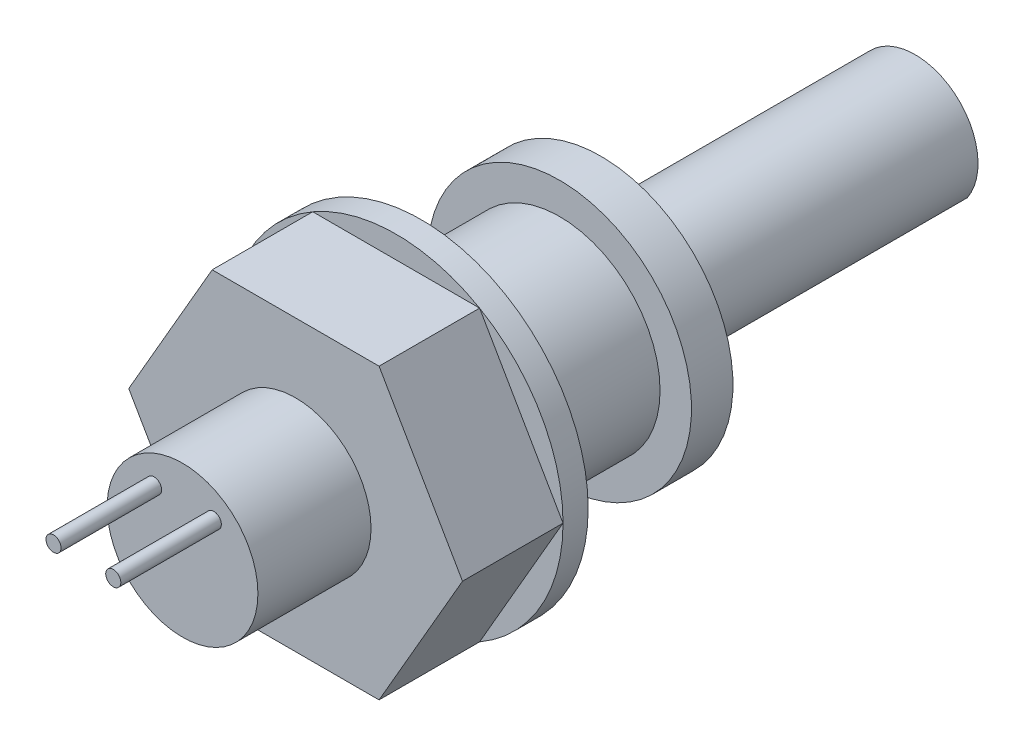
SolidWorks part; units mm, degrees
ref_plane "Plano frontal" through (0, 0, 0) normal (0, 0, 1) x (1, 0, 0)
ref_plane "Plano superior" through (0, 0, 0) normal (0, 1, 0) x (1, 0, 0)
ref_plane "Plano direito" through (0, 0, 0) normal (1, 0, 0) x (0, 0, -1)
sketch "Esboço1" plane through (0, 0, 0) normal (0, 0, 1) x (1, 0, 0)
  line L1 (6.6395, -11.5) -> (13.2791, 0)
  line L2 (13.2791, 0) -> (6.6395, 11.5)
  line L3 (6.6395, 11.5) -> (-6.6395, 11.5)
  line L4 (-6.6395, 11.5) -> (-13.2791, 0)
  line L5 (-13.2791, 0) -> (-6.6395, -11.5)
  line L6 (-6.6395, -11.5) -> (6.6395, -11.5)
  circle A0 centre (0, 0) radius 11.5 construction
  dimension "D1" = 23
extrude "Ressalto-extrusão1" add sketch "Esboço1" along normal blind 8
sketch "Esboço2" plane through (0, 0, 8) normal (0, 0, 1) x (1, 0, 0)
  circle A0 centre (0, 0) radius 6
extrude "Ressalto-extrusão2" add sketch "Esboço2" along normal blind 9
sketch "Esboço3" plane through (0, 0, 0) normal (0, 0, -1) x (-1, 0, 0)
  circle A0 centre (0, 0) radius 8
extrude "Ressalto-extrusão3" add sketch "Esboço3" along normal blind 13
sketch "Esboço4" plane through (0, 0, -13) normal (0, 0, -1) x (-1, 0, 0)
  circle A0 centre (0, 0) radius 10.5
  dimension "D1" = 21
extrude "Ressalto-extrusão4" add sketch "Esboço4" along normal blind 3.3
sketch "Esboço5" plane through (0, 0, -16.3) normal (0, 0, -1) x (-1, 0, 0)
  line L0 (-4.1481, -2.7916) -> (4.1481, -2.7916)
  arc A0 (4.1481, -2.7916) -> (-4.1481, -2.7916) centre (0, 0) ccw
  dimension "D1" = 10
extrude "Ressalto-extrusão6" add sketch "Esboço5" along normal blind 25
sketch "Esboço6" plane through (0, 0, 0) normal (0, 0, -1) x (-1, 0, 0)
  circle A0 centre (0, 0) radius 13.2791
extrude "Ressalto-extrusão7" add sketch "Esboço6" along normal blind 2
sketch "Esboço7" plane through (0, 0, 17) normal (0, 0, 1) x (1, 0, 0)
  circle A0 centre (-2.2638, 3.3202) radius 0.6
  circle A1 centre (2.4902, 3.3202) radius 0.6
  dimension "D1" = 1.2
extrude "Ressalto-extrusão8" add sketch "Esboço7" along normal blind 8
